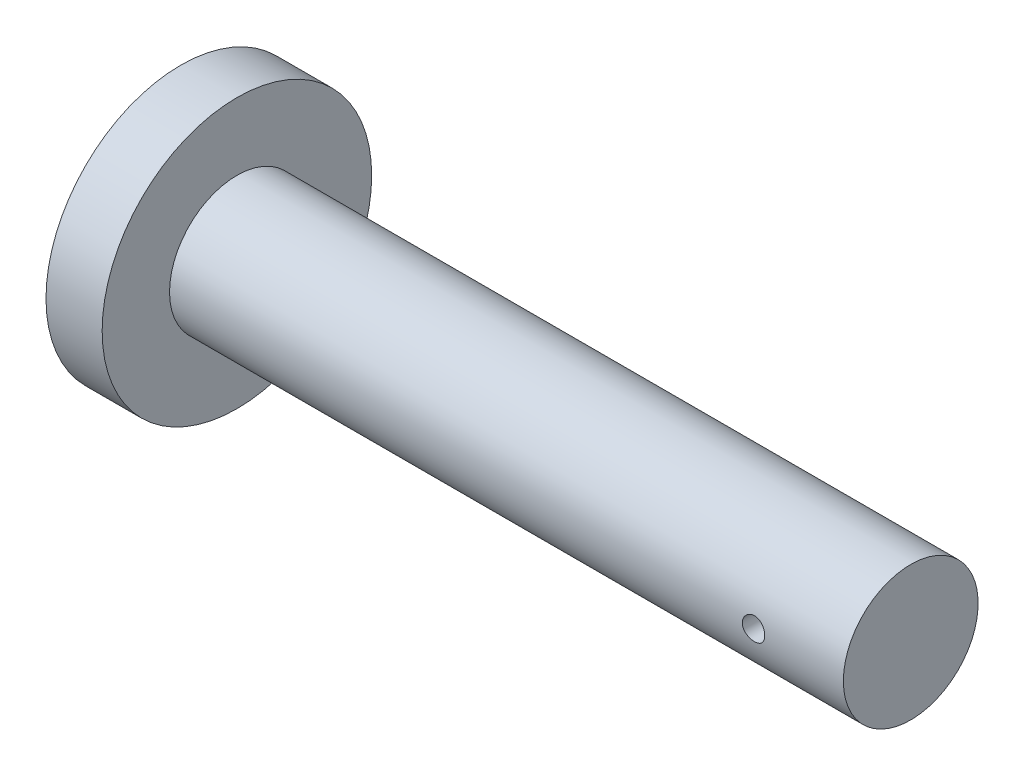
SolidWorks part; units mm, degrees
ref_plane "Front Plane" through (0, 0, 0) normal (0, 0, 1) x (1, 0, 0)
ref_plane "Top Plane" through (0, 0, 0) normal (0, 1, 0) x (1, 0, 0)
ref_plane "Right Plane" through (0, 0, 0) normal (1, 0, 0) x (0, 0, -1)
sketch "Sketch1" plane through (0, 0, 0) normal (0, 0, 1) x (1, 0, 0)
  line L0 (0, 0) -> (25807.5528, 0) construction
  line L1 (0, 0) -> (0, 25807.5528) construction
  line L2 (-27.9859, 12) -> (-27.9859, 0)
  line L3 (-27.9859, 12) -> (-22.9859, 12)
  line L4 (-22.9859, 12) -> (-22.9859, 6)
  line L5 (-22.9859, 6) -> (37.0141, 6)
  line L6 (37.0141, 6) -> (37.0141, 0)
  line L7 (37.0141, 0) -> (-27.9859, 0)
  point P8 (-23.7183, 0)
  dimension "D1" = 12
  dimension "D2" = 6
  dimension "D3" = 5
  dimension "D4" = 60
revolve "Revolve1" add sketch "Sketch1" angle 360 about L0
sketch "Sketch2" plane through (0, 0, 0) normal (0, 0, 1) x (1, 0, 0)
  line L0 (37.0141, -6) -> (37.0141, 6) construction
  circle A0 centre (29.0141, 0) radius 1
  dimension "D1" = 2
  dimension "D2" = 8
extrude "Cut-Extrude1" cut sketch "Sketch2" against normal through all both and the other way through all
